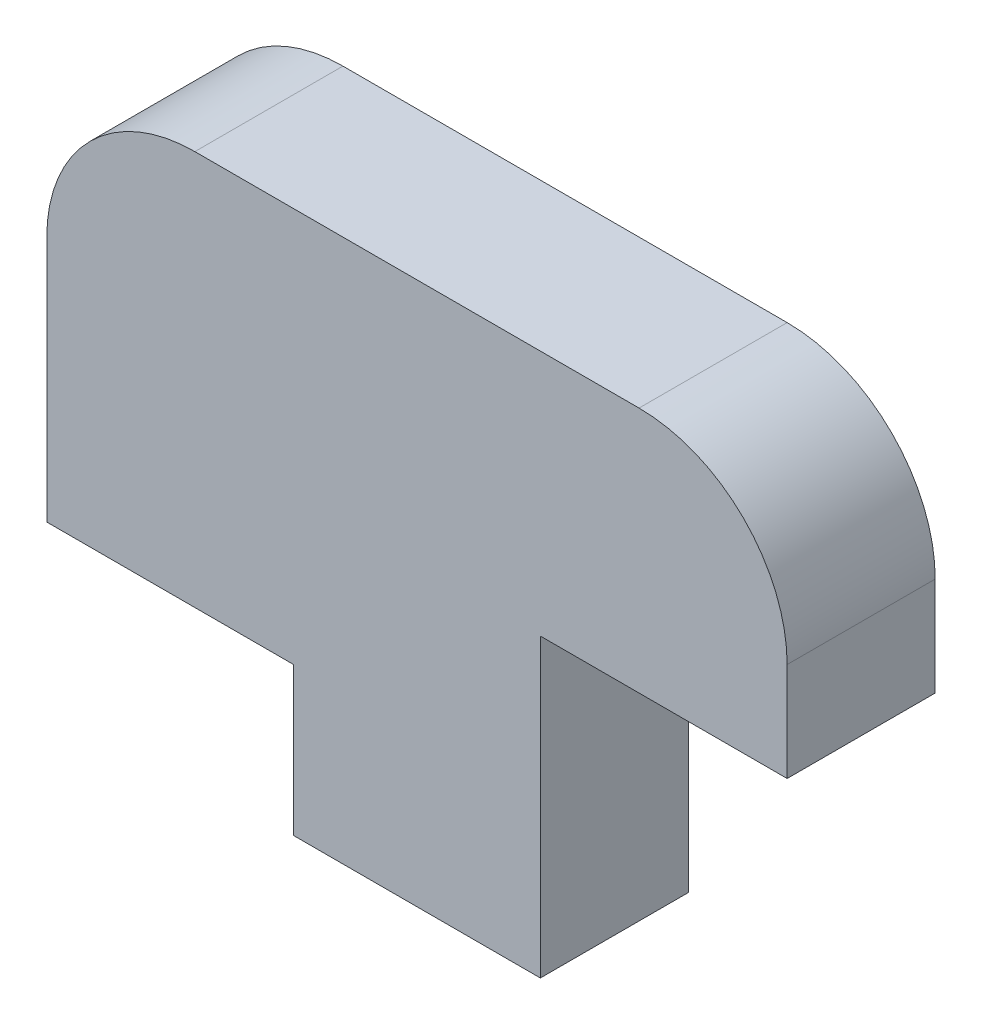
SolidWorks part; units mm, degrees
material "ABS PC"
ref_plane "Front Plane" through (0, 0, 0) normal (0, 0, 1) x (1, 0, 0)
ref_plane "Top Plane" through (0, 0, 0) normal (0, 1, 0) x (1, 0, 0)
ref_plane "Right Plane" through (0, 0, 0) normal (1, 0, 0) x (0, 0, -1)
sketch "Sketch1" plane through (0, 0, 0) normal (0, 0, 1) x (1, 0, 0)
  line L0 (-5, 3) -> (-5, 0)
  line L1 (-5, 0) -> (0, 0)
  line L2 (0, 0) -> (0, 6)
  line L4 (-5, 3) -> (-10, 3)
  line L5 (-10, 3) -> (-10, 8)
  line L6 (-7, 11) -> (2, 11)
  line L8 (5, 6) -> (0, 6)
  line L9 (5, 6) -> (5, 8)
  arc A0 (5, 8) -> (2, 11) centre (2, 8) ccw
  arc A1 (-7, 11) -> (-10, 8) centre (-7, 8) ccw
  dimension "D4" = 3
  dimension "D5" = 3
  dimension "D1" = 3
  dimension "D2" = 3
  dimension "D3" = 8
  dimension "D6" = 5
  dimension "D7" = 5
  dimension "D8" = 5
extrude "Boss-Extrude1" add sketch "Sketch1" along normal blind 3
